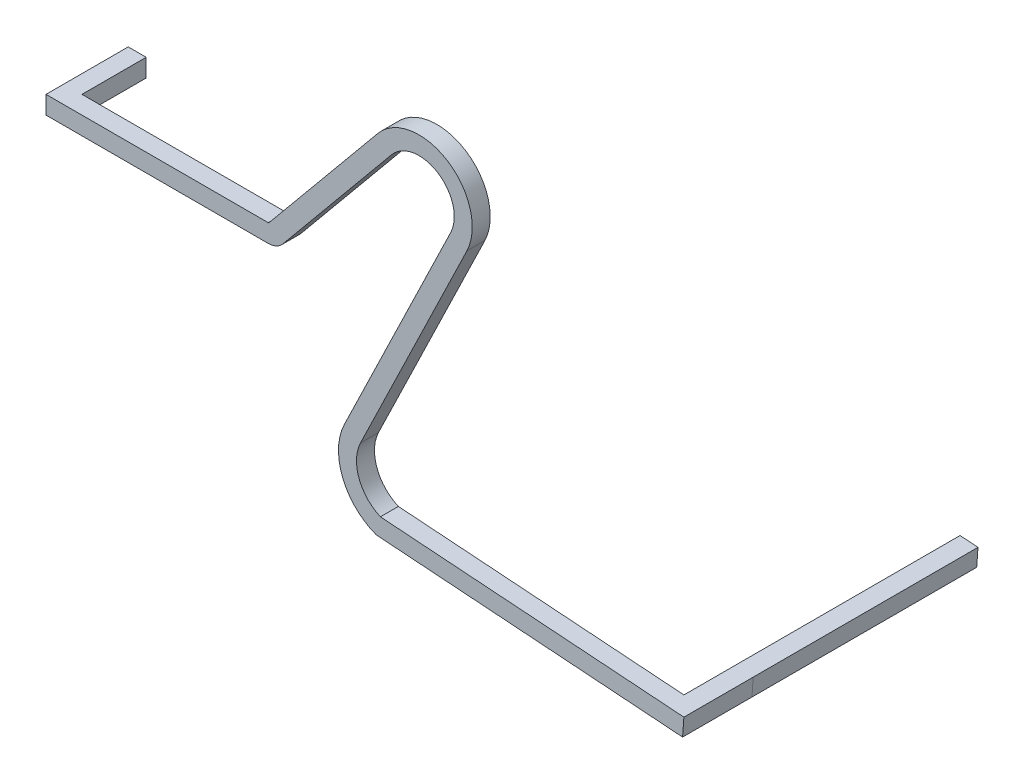
SolidWorks part; units mm, degrees
ref_plane "Ön Düzlem" through (0, 0, 0) normal (0, 0, 1) x (1, 0, 0)
ref_plane "Üst Düzlem" through (0, 0, 0) normal (0, 1, 0) x (1, 0, 0)
ref_plane "Sağ Düzlem" through (0, 0, 0) normal (1, 0, 0) x (0, 0, -1)
sketch "Çizim1" plane through (0, 0, 0) normal (0, 0, 1) x (1, 0, 0)
  line L0 (0, 0) -> (34.5871, 0)
  line L1 (36.8999, 1.0893) -> (53.8333, 21.5864)
  line L2 (51.434, -30.8957) -> (99.1276, -34.3156)
  line L3 (63.0227, 15.6844) -> (46.4476, -18.5101)
  line L4 (0, 2.8) -> (34.5871, 2.8)
  line L5 (34.7413, 2.8726) -> (51.6747, 23.3697)
  line L6 (65.5423, 14.463) -> (48.9671, -19.7315)
  line L7 (52.0689, -28.134) -> (99.3279, -31.5228)
  line L8 (0, 2.8) -> (0, 0)
  line L9 (99.3279, -31.5228) -> (99.1276, -34.3156)
  arc A0 (34.5871, 0) -> (36.8999, 1.0893) centre (34.5871, 3) ccw
  arc A1 (63.0227, 15.6844) -> (53.8333, 21.5864) centre (58.0735, 18.0834) ccw
  arc A2 (46.4476, -18.5101) -> (51.434, -30.8957) centre (54.5579, -22.4415) ccw
  arc A3 (34.5871, 2.8) -> (34.7413, 2.8726) centre (34.5871, 3) ccw
  arc A4 (65.5423, 14.463) -> (51.6747, 23.3697) centre (58.0735, 18.0834) ccw
  arc A5 (48.9671, -19.7315) -> (52.0689, -28.134) centre (54.5579, -22.4415) ccw
  point P6 (36, 0)
  point P9 (99.1276, -34.3156)
  point P10 (51.434, -30.8957)
  dimension "D3" = 3
  dimension "D5" = 11
  dimension "D1" = 36
  dimension "D2" = 28
  dimension "D4" = 58
  dimension "D6" = 38
  dimension "D7" = 50
  dimension "D8" = 55
  dimension "D9" = 50
  dimension "D10" = 48
  dimension "D11" = 60
  dimension "D12" = 2.8
extrude "Yükseklik-Ekstrüzyon1" add sketch "Çizim1" along normal blind 2.8
sketch "Çizim2" plane through (0, 0, 0) normal (0, 0, -1) x (-1, 0, 0)
  line L0 (0, 2.8) -> (0, 0)
  line L1 (0, 2.8) -> (-2.8, 2.8)
  line L2 (0, 0) -> (-2.8, 0)
  line L3 (-2.8, 2.8) -> (-2.8, 0)
  dimension "D1" = 2.8
extrude "Yükseklik-Ekstrüzyon3" add sketch "Çizim2" along normal blind 45
sketch "Çizim3" plane through (0, 0, 0) normal (0, 0, -1) x (-1, 0, 0)
  line L0 (-99.3279, -31.5228) -> (-99.1276, -34.3156)
  line L1 (-99.3279, -31.5228) -> (-96.535, -31.3225)
  line L2 (-99.1276, -34.3156) -> (-96.3348, -34.1154)
  line L3 (-96.535, -31.3225) -> (-96.3348, -34.1154)
  dimension "D1" = 2.8
extrude "Yükseklik-Ekstrüzyon4" add sketch "Çizim3" along normal blind 8
sketch "Çizim4" plane through (0, 0, -45) normal (0, 0, -1) x (-1, 0, 0)
  line L0 (0, 2.8) -> (-2.8, 2.8)
  line L1 (0, 2.8) -> (0, -0.0037)
  line L2 (-2.8, 2.8) -> (-2.8, -0.0037)
  line L3 (0, -0.0037) -> (-2.8, -0.0037)
extrude "Kes-Ekstrüzyon1" cut sketch "Çizim4" against normal blind 35
sketch "Çizim5" plane through (0, 0, -8) normal (0, 0, -1) x (-1, 0, 0)
  line L0 (-96.535, -31.3225) -> (-96.3348, -34.1154)
  line L1 (-96.535, -31.3225) -> (-99.3275, -31.5228)
  line L2 (-96.3348, -34.1154) -> (-99.1273, -34.3156)
  line L3 (-99.3275, -31.5228) -> (-99.1273, -34.3156)
extrude "Yükseklik-Ekstrüzyon5" add sketch "Çizim5" along normal blind 35
